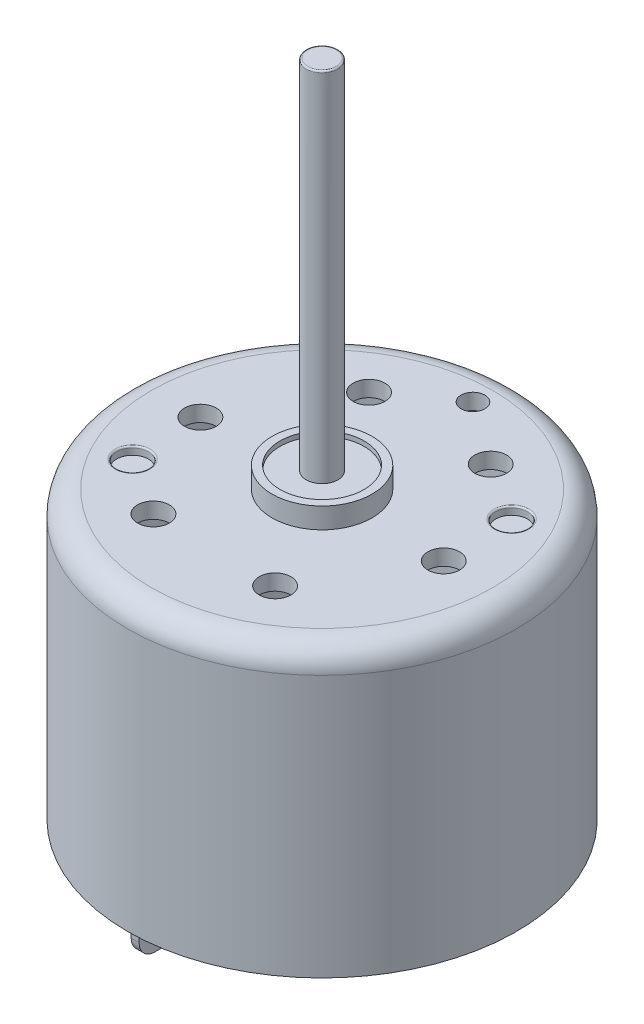
SolidWorks part; units mm, degrees
material "AISI 1020"
ref_plane "Front Plane" through (0, 0, 0) normal (0, 0, 1) x (1, 0, 0)
ref_plane "Top Plane" through (0, 0, 0) normal (0, 1, 0) x (1, 0, 0)
ref_plane "Right Plane" through (0, 0, 0) normal (1, 0, 0) x (0, 0, -1)
sketch "Sketch1" plane through (0, 0, 0) normal (0, 1, 0) x (1, 0, 0)
  circle A0 centre (0, 0) radius 12.25
extrude "Boss-Extrude1" add sketch "Sketch1" along normal blind 18
sketch "Sketch2" plane through (0, 18, 0) normal (0, 1, 0) x (1, 0, 0)
  circle A0 centre (0, 0) radius 3.15
extrude "Boss-Extrude2" add sketch "Sketch2" along normal blind 1.3
sketch "Sketch3" plane through (0, 19.3, 0) normal (0, 1, 0) x (1, 0, 0)
  circle A1 centre (0, 0) radius 2.65
extrude "Cut-Extrude1" cut sketch "Sketch3" against normal blind 0.3
sketch "Sketch4" plane through (0, 19, 0) normal (0, 1, 0) x (1, 0, 0)
  circle A0 centre (0, 0) radius 1
extrude "Boss-Extrude3" add sketch "Sketch4" along normal blind 22.5
sketch "Sketch5" plane through (0, 0, 0) normal (0, -1, 0) x (1, 0, 0)
  circle A1 centre (0, 0) radius 11.75
extrude "Cut-Extrude2" cut sketch "Sketch5" against normal blind 0.5
sketch "Sketch6" plane through (0, 0.5, 0) normal (0, -1, 0) x (1, 0, 0)
  circle A0 centre (0, 0) radius 3.25
extrude "Boss-Extrude4" add sketch "Sketch6" along normal blind 2.2
sketch "Sketch7" plane through (0, 0.5, 0) normal (0, -1, 0) x (1, 0, 0)
  line L1 (-2.0186, -10.7483) -> (1.9814, -10.7483)
  line L2 (-3.0186, -9.7483) -> (-3.0186, -8.7483)
  line L3 (-2.0186, -7.7483) -> (1.9814, -7.7483)
  line L4 (2.9814, -9.7483) -> (2.9814, -8.7483)
  line L5 (2.9814, 9.7483) -> (2.9814, 8.7483)
  line L6 (-2.0186, 7.7483) -> (1.9814, 7.7483)
  line L7 (-3.0186, 9.7483) -> (-3.0186, 8.7483)
  line L8 (-2.0186, 10.7483) -> (1.9814, 10.7483)
  circle A2 centre (0, 0) radius 12.25 construction
  arc A3 (2.9814, -8.7483) -> (1.9814, -7.7483) centre (1.9814, -8.7483) ccw
  arc A4 (2.9814, -9.7483) -> (1.9814, -10.7483) centre (1.9814, -9.7483) cw
  arc A5 (-2.0186, -7.7483) -> (-3.0186, -8.7483) centre (-2.0186, -8.7483) ccw
  arc A6 (-2.0186, -10.7483) -> (-3.0186, -9.7483) centre (-2.0186, -9.7483) cw
  circle A7 centre (-5.1258, -8.5864) radius 1.25
  circle A8 centre (5.0886, -8.5864) radius 1.25
  circle A9 centre (5.0886, 8.5864) radius 1.25
  circle A10 centre (-5.1258, 8.5864) radius 1.25
  arc A11 (-2.0186, 10.7483) -> (-3.0186, 9.7483) centre (-2.0186, 9.7483) ccw
  arc A12 (-2.0186, 7.7483) -> (-3.0186, 8.7483) centre (-2.0186, 8.7483) cw
  arc A13 (2.9814, 9.7483) -> (1.9814, 10.7483) centre (1.9814, 9.7483) ccw
  arc A14 (2.9814, 8.7483) -> (1.9814, 7.7483) centre (1.9814, 8.7483) cw
  point P4 (0, -12.25)
  point P5 (-0.0186, -7.75)
  point P8 (-0.0186, -10.75)
  point P9 (-3.0186, -7.75)
  point P10 (2.9814, -7.7483)
  point P17 (2.9814, -7.7483)
  point P24 (0, 0)
  point P31 (-10, 0)
  point P35 (8.75, 0)
  point P43 (-5.1258, -8.5864)
  point P49 (2.9814, 7.7483)
  point P50 (-3.0186, 7.75)
  point P51 (-0.0186, 10.75)
  point P52 (-0.0186, 7.75)
  dimension "D1" = 4.5
  dimension "D5" = 1
  dimension "D2" = 3
  dimension "D3" = 3
  dimension "D4" = 3
extrude "Boss-Extrude5" add sketch "Sketch7" along normal blind 0.5
sketch "Sketch8" plane through (0, 0, 0) normal (0, -1, 0) x (1, 0, 0)
  circle A0 centre (-5.1258, -8.5864) radius 1.25
  circle A1 centre (5.0886, -8.5864) radius 1.25
  circle A2 centre (5.0886, 8.5864) radius 1.25
  circle A3 centre (-5.1258, 8.5864) radius 1.25
extrude "Cut-Extrude3" cut sketch "Sketch8" against normal blind 0.25
sketch "Sketch9" plane through (0, 0.5, 0) normal (0, -1, 0) x (1, 0, 0)
  line L0 (-2.63, 2.9404) -> (-3.0304, 3.3881)
  line L1 (1.578, 3.6156) -> (1.8182, 4.1661)
  line L2 (2.63, -2.9404) -> (3.0304, -3.3881)
  line L3 (-1.578, -3.6156) -> (-1.8182, -4.1661)
  arc A0 (-1.3241, -3.5085) -> (2.3553, -2.9181) centre (0, 0) ccw
  arc A1 (-1.7068, -4.4328) -> (3.008, -3.6762) centre (0, 0) ccw
  arc A2 (1.3241, 3.5085) -> (-2.3553, 2.9181) centre (0, 0) ccw
  arc A3 (1.7068, 4.4328) -> (-3.008, 3.6762) centre (0, 0) ccw
  arc A4 (-2.63, 2.9404) -> (-2.3553, 2.9181) centre (-2.4809, 3.0737) ccw
  arc A5 (-3.0304, 3.3881) -> (-3.008, 3.6762) centre (-2.8813, 3.5214) cw
  arc A6 (1.8182, 4.1661) -> (1.7068, 4.4328) centre (1.6349, 4.2461) ccw
  arc A7 (1.578, 3.6156) -> (1.3241, 3.5085) centre (1.3947, 3.6956) cw
  arc A8 (2.63, -2.9404) -> (2.3553, -2.9181) centre (2.4809, -3.0737) ccw
  arc A9 (3.0304, -3.3881) -> (3.008, -3.6762) centre (2.8813, -3.5214) cw
  arc A10 (-1.578, -3.6156) -> (-1.3241, -3.5085) centre (-1.3947, -3.6956) cw
  arc A11 (-1.8182, -4.1661) -> (-1.7068, -4.4328) centre (-1.6349, -4.2461) ccw
  circle A14 centre (-5.7163, -3.0942) radius 0.75
  circle A15 centre (5.6829, 3.1551) radius 0.75
  point P6 (-2.5, 2.7951)
  point P7 (1.5, 3.4369)
  point P12 (2.5, -2.7951)
  point P13 (-1.5, -3.4369)
  point P16 (-2.5, 2.7951)
  point P21 (1.9, 4.3534)
  point P24 (1.5, 3.4369)
  point P27 (2.5, -2.7951)
  point P34 (7.25, 0)
  point P35 (0, 0)
  point P39 (-5.7163, -3.0942)
  point P42 (5.4988, 1.6811)
  dimension "D1" = 0.2
extrude "Cut-Extrude4" cut sketch "Sketch9" against normal blind 5
ref_plane "Plane1" through (0, 17, 0) normal (0, 1, 0) x (1, 0, 0)
sketch "Sketch10" plane through (0, 17, 0) normal (0, 1, 0) x (1, 0, 0)
  circle A1 centre (0, 0) radius 11.25
extrude "Cut-Extrude5" cut sketch "Sketch10" against normal blind 16
sketch "Sketch11" plane through (0, 0, 0) normal (0, -1, 0) x (1, 0, 0)
  line L0 (2.9814, -9.7483) -> (2.9814, -8.7483) construction
  line L1 (-3.0186, 9.7483) -> (-3.0186, 8.7483) construction
  line L2 (1.4814, -10.4983) -> (1.4814, -7.9983)
  line L3 (0.9814, -7.9983) -> (0.9814, -10.4983)
  line L4 (1.4814, -7.9983) -> (0.9814, -7.9983)
  line L5 (-1.0186, 10.4983) -> (-1.5186, 10.4983)
  line L6 (1.4814, -10.4983) -> (0.9814, -10.4983)
  line L7 (-1.0186, 7.9983) -> (-1.5186, 7.9983)
  line L8 (-1.0186, 10.4983) -> (-1.0186, 7.9983)
  line L9 (-1.5186, 7.9983) -> (-1.5186, 10.4983)
  point P0 (2.9814, -9.2483)
  point P1 (1.4814, -9.2483)
  point P4 (-3.0186, 9.2483)
  point P5 (-1.5186, 9.2483)
  point P8 (0.9814, -9.2483)
  point P9 (-1.0186, 9.2483)
  dimension "D1" = 1.5
  dimension "D2" = 1.5
  dimension "D3" = 0.5
  dimension "D4" = 0.5
extrude "Boss-Extrude6" add sketch "Sketch11" along normal blind 3
sketch "Sketch12" plane through (0.9814, 0, 0) normal (-1, 0, 0) x (0, 0, 1)
  line L1 (9.4983, -3) -> (8.9983, -3)
  line L6 (-8.9983, -3) -> (-9.4983, -3)
  line L11 (10.4983, -3) -> (7.9983, -3)
  line L12 (10.4983, -3) -> (10.4983, -2)
  line L14 (7.9983, -3) -> (7.9983, -2)
  line L15 (-7.9983, -3) -> (-10.4983, -3)
  line L16 (-7.9983, -3) -> (-7.9983, -2)
  line L18 (-10.4983, -3) -> (-10.4983, -2)
  arc A0 (-10.4983, -2) -> (-9.4983, -3) centre (-9.4983, -2) ccw
  arc A1 (-7.9983, -2) -> (-8.9983, -3) centre (-8.9983, -2) cw
  arc A2 (7.9983, -2) -> (8.9983, -3) centre (8.9983, -2) ccw
  arc A3 (10.4983, -2) -> (9.4983, -3) centre (9.4983, -2) cw
  circle A4 centre (9.2483, -2) radius 0.5
  circle A5 centre (-9.2483, -2) radius 0.5
  point P18 (-7.9983, -3)
  point P23 (10.4983, -3)
  line M2 (-10.4983, 0) -> (-10.4983, -3)
  line M3 (-10.4983, -3) -> (-7.9983, -3)
  line M4 (-7.9983, -3) -> (-7.9983, 0)
  dimension "D1" = 1
extrude "Cut-Extrude6" cut sketch "Sketch12" against normal blind 3 and the other way blind 5 contours A0 M2 M3 | A1 M4 M3 | A5 | A2 L14 L11 | L12 A3 L11 | A4
fillet "Fillet1" radius 1.5 1 edges at (0, 18, 12.25)
fillet "Fillet2" radius 1 1 edges at (0, -1.7, -3.25)
sketch "Sketch13" plane through (0, 18, 0) normal (0, 1, 0) x (1, 0, 0)
  circle A2 centre (3.9512, 6.6671) radius 1
  circle A3 centre (7.7495, -0.0883) radius 1
  circle A4 centre (3.7983, -6.7554) radius 1
  circle A5 centre (-3.9512, -6.6671) radius 1
  circle A6 centre (-7.7495, 0.0883) radius 1
  circle A7 centre (-3.7983, 6.7554) radius 1
  circle A9 centre (0, 9.5) radius 0.75
  point P0 (0, 0)
  point P6 (6.4551, 1.9735)
  point P19 (0, 0)
  point P20 (0, 0)
  point P24 (0, 0)
  dimension "D2" = 6
extrude "Cut-Extrude7" cut sketch "Sketch13" against normal blind 3
sketch "Sketch14" plane through (0, 18, 0) normal (0, 1, 0) x (1, 0, 0)
  circle A6 centre (7.6025, 4.3318) radius 1
  circle A7 centre (-7.6025, -4.3318) radius 1
  point P0 (0, 0)
  point P4 (0, 0)
  point P5 (7.4114, 2.2659)
  point P6 (9.75, 0)
extrude "Cut-Extrude8" cut sketch "Sketch14" against normal blind 0.5
fillet "Fillet4" radius 0.1 2 edges at (-7.6025, 18, 5.3318) (7.6025, 18, -3.3318)
fillet "Fillet5" radius 0.1 1 edges at (0, 41.5, 1)
